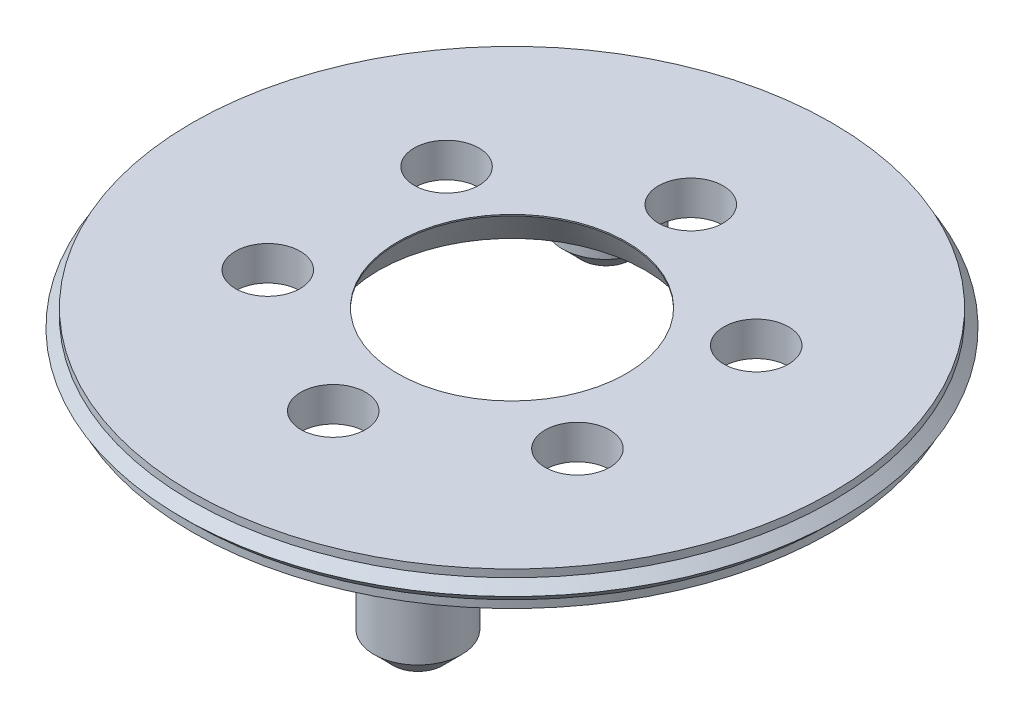
SolidWorks part; units mm, degrees
ref_plane "Front Plane" through (0, 0, 0) normal (0, 0, 1) x (1, 0, 0)
ref_plane "Top Plane" through (0, 0, 0) normal (0, 1, 0) x (1, 0, 0)
ref_plane "Right Plane" through (0, 0, 0) normal (1, 0, 0) x (0, 0, -1)
sketch "Sketch1" plane through (0, 0, 0) normal (0, 0, 1) x (1, 0, 0)
  line L0 (6, -0.9) -> (16.8, -0.9)
  line L1 (16.8, -0.9) -> (16.8, -0.5)
  line L2 (16.8, -0.5) -> (17.3, 0)
  line L3 (17.3, 0) -> (16.8, 0.5)
  line L4 (16.8, 0.5) -> (16.8, 0.9)
  line L5 (16.8, 0.9) -> (6, 0.9)
  line L6 (6, 0.9) -> (6, -0.9)
  line L7 (0, -175.2074) -> (0, 8585.1618) construction
  point P9 (16.6523, -0.0388)
  point P11 (17.7272, 0.3929)
  point P12 (16.8192, 0.1325)
  point P13 (16.8392, 0)
  point P14 (16.8, 1.835)
  point P15 (16.8, 1.2541)
  point P16 (0, 0)
  point P17 (6, 0)
  point P18 (0, 0)
  dimension "D1" = 12
  dimension "D2" = 33.6
  dimension "D3" = 1
  dimension "D4" = 0.5
  dimension "D5" = 1.8
revolve "Revolve1" add sketch "Sketch1" angle 360 about L7
sketch "Sketch2" plane through (0, 0.9, 0) normal (0, 1, 0) x (1, 0, 0)
  circle A0 centre (0, 0) radius 9.385 construction
  circle A1 centre (0, 9.385) radius 1.7
  circle A2 centre (8.1276, 4.6925) radius 1.7
  circle A3 centre (8.1276, -4.6925) radius 1.7
  circle A4 centre (0, -9.385) radius 1.7
  circle A5 centre (-8.1276, -4.6925) radius 1.7
  circle A6 centre (-8.1276, 4.6925) radius 1.7
  point P6 (-8.126, 4.6953)
  point P7 (-8.0413, -6.3661)
  point P17 (0, 0)
  point P18 (0, 0)
  dimension "D1" = 18.77
  dimension "D2" = 3.4
  dimension "D3" = 6
extrude "Cut-Extrude1" cut sketch "Sketch2" against normal through all
sketch "Sketch3" plane through (0, -0.9, 0) normal (0, -1, 0) x (1, 0, 0)
  line L0 (-1000, 0) -> (49000, 0) construction
  line L1 (0, 0) -> (25000, 43301.2702) construction
  circle A0 centre (0, 0) radius 13.5 construction
  circle A1 centre (6.75, 11.6913) radius 2.3
  circle A2 centre (-6.75, -11.6913) radius 2.3
  dimension "D1" = 27
  dimension "D3" = 4.6
  dimension "D2" = 60
extrude "Boss-Extrude1" add sketch "Sketch3" along normal blind 4.6
chamfer "Chamfer1" distance 1 angle 45 2 edges at (-4.45, -5.5, -11.6913) (9.05, -5.5, 11.6913)
chamfer "Chamfer2" distance 1 angle 60 1 edges at (6, -0.9, 0)
equation "\"wire_input_hole_dia\" = 12mm"
equation "\"bolt_retaining_disk_dia\" = 34mm"
equation "\"V-slot_depth\" = 0.5mm"
equation "\"V-slot-width\" = 1mm"
equation "\"D1@Sketch1\"=\"wire_input_hole_dia\""
equation "\"Clearance_offset\" = 0.2mm"
equation "\"interference_offset\" = 0.1mm"
equation "\"D2@Sketch1\"=\"bolt_retaining_disk_dia\"-\"Clearance_offset\"*2"
equation "\"D3@Sketch1\"=\"V-slot-width\""
equation "\"D4@Sketch1\"=\"V-slot_depth\""
equation "\"Retaining_disk_thickness\" = 2mm"
equation "\"D5@Sketch1\"=\"Retaining_disk_thickness\"-\"Clearance_offset\""
equation "\"D3@Sketch3\"=5-2*\"Clearance_offset\""
